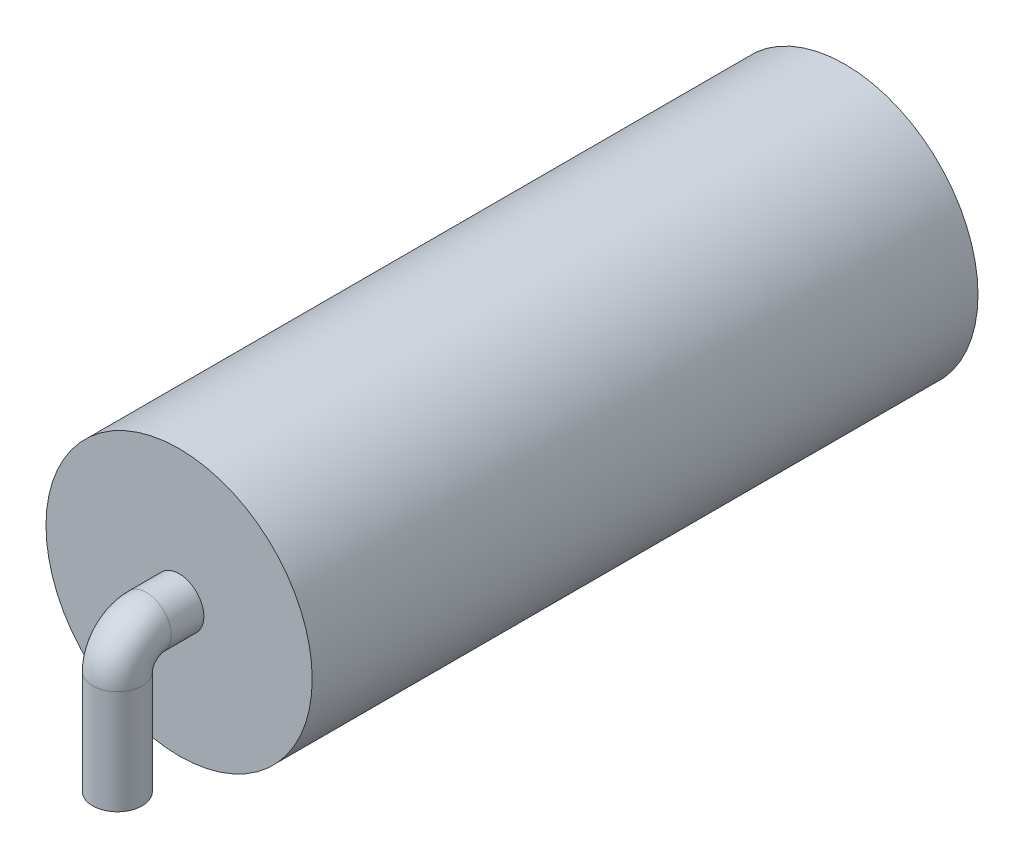
SolidWorks part; units mm, degrees
ref_plane "Front Plane" through (0, 0, 0) normal (0, 0, 1) x (1, 0, 0)
ref_plane "Top Plane" through (0, 0, 0) normal (0, 1, 0) x (1, 0, 0)
ref_plane "Right Plane" through (0, 0, 0) normal (1, 0, 0) x (0, 0, -1)
sketch "Sketch1" plane through (0, 0, 0) normal (0, 0, 1) x (1, 0, 0)
  circle A0 centre (0, 0) radius 2.285
  dimension "D1" = 4.57
extrude "Boss-Extrude1" add sketch "Sketch1" along normal mid plane 11.43 contours A0
sketch "Sketch2" plane through (0, 0, 0) normal (1, 0, 0) x (0, 0, -1)
  line L0 (6.275, 0) -> (-6.275, 0)
  line L1 (-6.775, -0.5) -> (-6.775, -2.285)
  line L2 (0, 0) -> (0, -3.5108) construction
  line L4 (6.775, -0.5) -> (6.775, -2.285)
  line L5 (-5.715, -2.285) -> (5.715, -2.285) construction
  arc A0 (-6.275, 0) -> (-6.775, -0.5) centre (-6.275, -0.5) ccw
  arc A1 (6.275, 0) -> (6.775, -0.5) centre (6.275, -0.5) cw
  point P5 (0, 0)
  point P14 (0, 0)
  dimension "D1" = 13.55
  dimension "D2" = 0.5
sweep "Sweep1" add path "Sketch2" circular profile diameter 0.85 parameters "D3"=0.85
